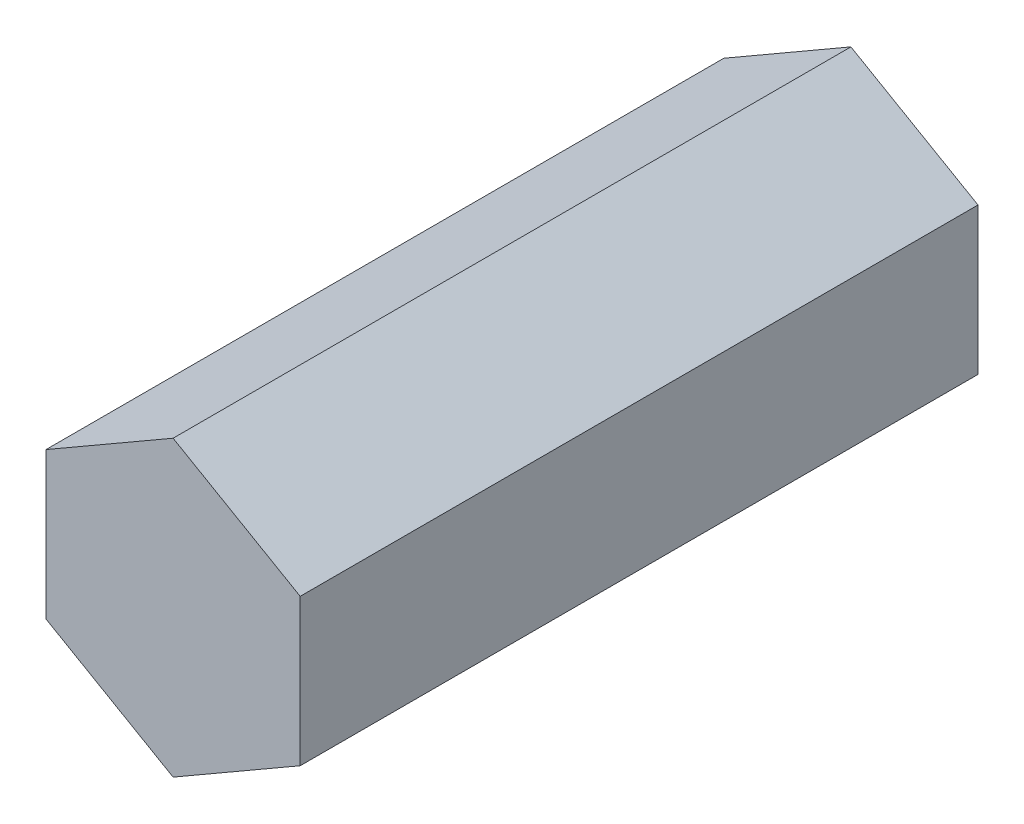
SolidWorks part; units mm, degrees
ref_plane "前视基准面" through (0, 0, 0) normal (0, 0, 1) x (1, 0, 0)
ref_plane "上视基准面" through (0, 0, 0) normal (0, 1, 0) x (1, 0, 0)
ref_plane "右视基准面" through (0, 0, 0) normal (1, 0, 0) x (0, 0, -1)
other "Configuration Table"
sketch "草图2" plane through (0, 0, 0) normal (0, 0, 1) x (1, 0, 0)
  line L0 (0, 0) -> (0, 3.0916) construction
  line L1 (0, 1.7321) -> (-1.5, 0.866)
  line L2 (-1.5, 0.866) -> (-1.5, -0.866)
  line L3 (-1.5, -0.866) -> (0, -1.7321)
  line L4 (0, -1.7321) -> (1.5, -0.866)
  line L5 (1.5, -0.866) -> (1.5, 0.866)
  line L6 (1.5, 0.866) -> (0, 1.7321)
  circle A0 centre (0, 0) radius 1.5 construction
  dimension "D1" = 3
extrude "凸台-拉伸1" add sketch "草图2" along normal blind 8
